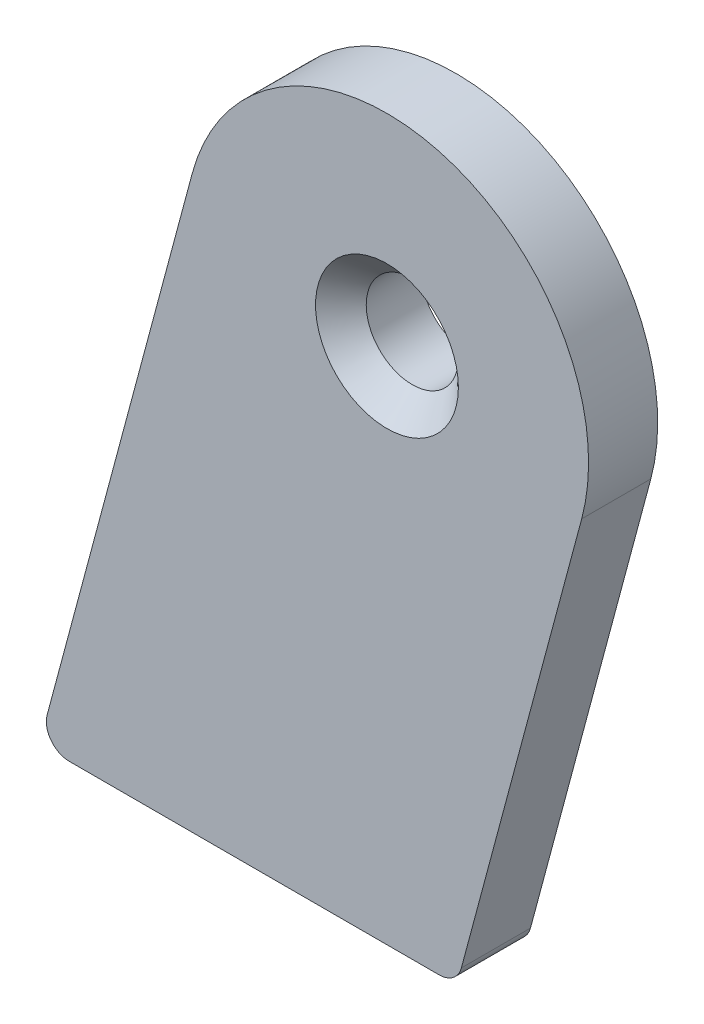
SolidWorks part; units mm, degrees
ref_plane "Ebene vorne" through (0, 0, 0) normal (0, 0, 1) x (1, 0, 0)
ref_plane "Ebene oben" through (0, 0, 0) normal (0, 1, 0) x (1, 0, 0)
ref_plane "Ebene rechts" through (0, 0, 0) normal (1, 0, 0) x (0, 0, -1)
sketch "Skizze1" plane through (0, 0, 0) normal (0, 1, 0) x (1, 0, 0)
  line L0 (52, -28) -> (52, -34) construction
  line L1 (48, -28) -> (48, -34) construction
  line L2 (48, -27) -> (48, -28) construction
  line L3 (46, -27) -> (46, -28) construction
  line L4 (34.5, -28) -> (34.5, -34) construction
  line L5 (46, -28) -> (34.5, -28) construction
  line L6 (34.5, -34) -> (48, -34) construction
  line L7 (48, -27) -> (46, -27) construction
  line L8 (52, -28) -> (52, -34) construction
  line L9 (48, -28) -> (48, -34)
  line L10 (48, -27) -> (48, -28)
  line L11 (46, -27) -> (46, -28)
  line L12 (34.5, -28) -> (34.5, -34)
  line L13 (46, -28) -> (34.5, -28)
  line L14 (34.5, -34) -> (48, -34)
  line L15 (48, -27) -> (46, -27)
revolve "Rotation1" add sketch "Skizze1" angle 360 about L8
sketch "Skizze2" plane through (0, 0, 34) normal (0, 0, 1) x (1, 0, 0)
  line L0 (21.825, -45) -> (58.0596, -45) construction
  line L1 (58.0596, -45) -> (68.9037, -4.5293) construction
  line L2 (35.0963, 4.5293) -> (21.825, -45) construction
  line L3 (21.825, -45) -> (58.0596, -45)
  line L4 (58.0596, -45) -> (68.9037, -4.5293)
  line L5 (35.0963, 4.5293) -> (21.825, -45)
  circle A0 centre (52, 0) radius 17.5 construction
  arc A1 (35.0963, 4.5293) -> (68.9037, -4.5293) centre (52, 0) ccw
extrude "Aufsatz-Linear austragen1" add sketch "Skizze2" against normal up to vertex
fillet "Verrundung1" radius 2 2 edges at (58.0596, -45, 31) (21.825, -45, 31)
hole_wizard "Formsenkung für M5 Linsensenkschraube mit Schlitz1" positions "Skizze3" profile "Skizze4" countersink size "M5" standard "DIN" end condition up to next
sketch "Skizze3" plane through (0, 0, 34) normal (0, 0, 1) x (1, 0, 0)
  point P0 (52, 0)
sketch "Skizze4" plane through (52, 0, 34) normal (1, 0, 0) x (0, -1, 0)
  line L0 (0, 0) -> (0, 7)
  line L1 (0, 7) -> (2.75, 7)
  line L2 (2.75, 7) -> (2.75, 3.45)
  line L3 (2.75, 3.45) -> (6.2, 0)
  line L5 (6.2, 0) -> (0, 0)
  line L6 (-2.75, 3.45) -> (-6.2, 0) construction
  line L11 (0, -6.35) -> (0, 107.95) construction
  dimension "Bohrerdurchmesser" = 5.5
  dimension "Bohrungstiefe" = 7
  dimension "Senkdurchmesser (Oben)" = 12.4
  dimension "Senkwinkel (Oben)" = 90
sketch "Skizze5" plane through (0, 0, 28) normal (0, 0, -1) x (-1, 0, 0)
  line L0 (-62.3294, -10.1761) -> (-61.0982, -8.5716) construction
  line L1 (-59.156, -12.6112) -> (-57.9248, -11.0067) construction
  line L2 (-62.3294, -10.1761) -> (-61.0982, -8.5716)
  line L3 (-59.156, -12.6112) -> (-57.9248, -11.0067)
  arc A0 (-60.827, 11.5036) -> (-60.827, -11.5036) centre (-52, 0) ccw construction
  arc A1 (-60.827, -11.5036) -> (-59.156, -12.6112) centre (-52, 0) ccw construction
  arc A2 (-57.9248, 11.0067) -> (-57.9248, -11.0067) centre (-52, 0) ccw construction
  arc A3 (-62.3294, -10.1761) -> (-60.827, -11.5036) centre (-52, 0) ccw
  arc A4 (-60.827, -11.5036) -> (-59.156, -12.6112) centre (-52, 0) ccw
  arc A5 (-61.0982, -8.5716) -> (-57.9248, -11.0067) centre (-52, 0) ccw
extrude "Aufsatz-Linear austragen2" add sketch "Skizze5" along normal up to vertex (3.5 mm away)
fillet "Verrundung2" radius 0.5 4 edges at (59.156, -12.6112, 26.25) (57.9248, -11.0067, 26.25) (61.0982, -8.5716, 26.25) (62.3294, -10.1761, 26.25)
